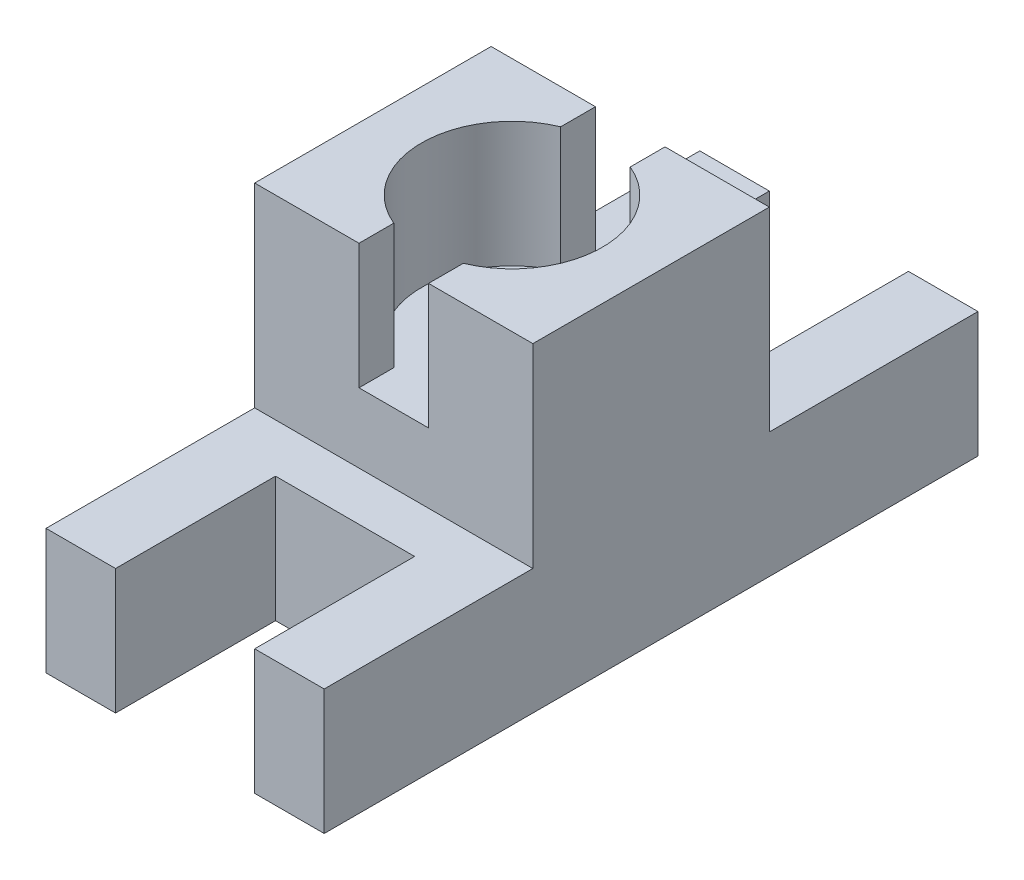
SolidWorks part; units mm, degrees
ref_plane "Alzado" through (0, 0, 0) normal (0, 0, 1) x (1, 0, 0)
ref_plane "Planta" through (0, 0, 0) normal (0, 1, 0) x (1, 0, 0)
ref_plane "Vista lateral" through (0, 0, 0) normal (1, 0, 0) x (0, 0, -1)
sketch "Croquis1" plane through (0, 0, 0) normal (1, 0, 0) x (0, 0, -1)
  line L1 (0, 0) -> (-94, 0)
  line L2 (0, 0) -> (0, 18)
  line L3 (-30, 46) -> (-64, 46)
  line L4 (-94, 0) -> (-94, 18)
  line L7 (-94, 18) -> (-64, 18)
  line L8 (-64, 46) -> (-64, 18)
  line L11 (0, 18) -> (-30, 18)
  line L12 (-30, 46) -> (-30, 18)
  point P1 (-47, 46)
  point P2 (-47, 0)
  dimension "D1" = 94
  dimension "D2" = 18
  dimension "D3" = 34
  dimension "D4" = 46
extrude "Saliente-Extruir1" add sketch "Croquis1" along normal mid plane 40
sketch "Croquis2" plane through (0, 18, 0) normal (0, 1, 0) x (1, 0, 0)
  line L0 (20, -94) -> (-20, -94) construction
  line L1 (-10, -94) -> (10, -94)
  line L2 (-10, -94) -> (-10, -71)
  line L3 (-10, -71) -> (10, -71)
  line L4 (10, -94) -> (10, -71)
  line L5 (20, -64) -> (-20, -64) construction
  line L6 (20, -47) -> (-14.9187, -47) construction
  line L7 (20, -30) -> (20, -64) construction
  line L8 (10, 0) -> (10, -23)
  line L9 (-10, 0) -> (10, 0)
  line L10 (-10, 0) -> (-10, -23)
  line L11 (-10, -23) -> (10, -23)
  point P6 (0, -71)
  point P9 (0, -64)
  dimension "D1" = 20
  dimension "D2" = 23
extrude "Cortar-Extruir1" cut sketch "Croquis2" against normal through all
sketch "Croquis3" plane through (0, 46, 0) normal (0, 1, 0) x (1, 0, 0)
  line L0 (5, -59) -> (5, -64)
  line L1 (20, -30) -> (-20, -30) construction
  line L2 (-20, -30) -> (-20, -64) construction
  line L3 (20, -30) -> (-20, -30) construction
  line L4 (-5, -30) -> (5, -30)
  line L5 (-5, -30) -> (-5, -35)
  line L6 (-5, -64) -> (5, -64)
  line L7 (5, -30) -> (5, -35)
  line L8 (20, -64) -> (-20, -64) construction
  line L9 (-5, -59) -> (-5, -64)
  arc A0 (-5, -35) -> (-5, -59) centre (0, -47) ccw
  arc A1 (5, -59) -> (5, -35) centre (0, -47) ccw
  point P1 (0, -64)
  point P8 (0, -30)
  point P9 (-20, -47)
  dimension "D1" = 26
  dimension "D2" = 10
extrude "Cortar-Extruir3" cut sketch "Croquis3" against normal blind 18
